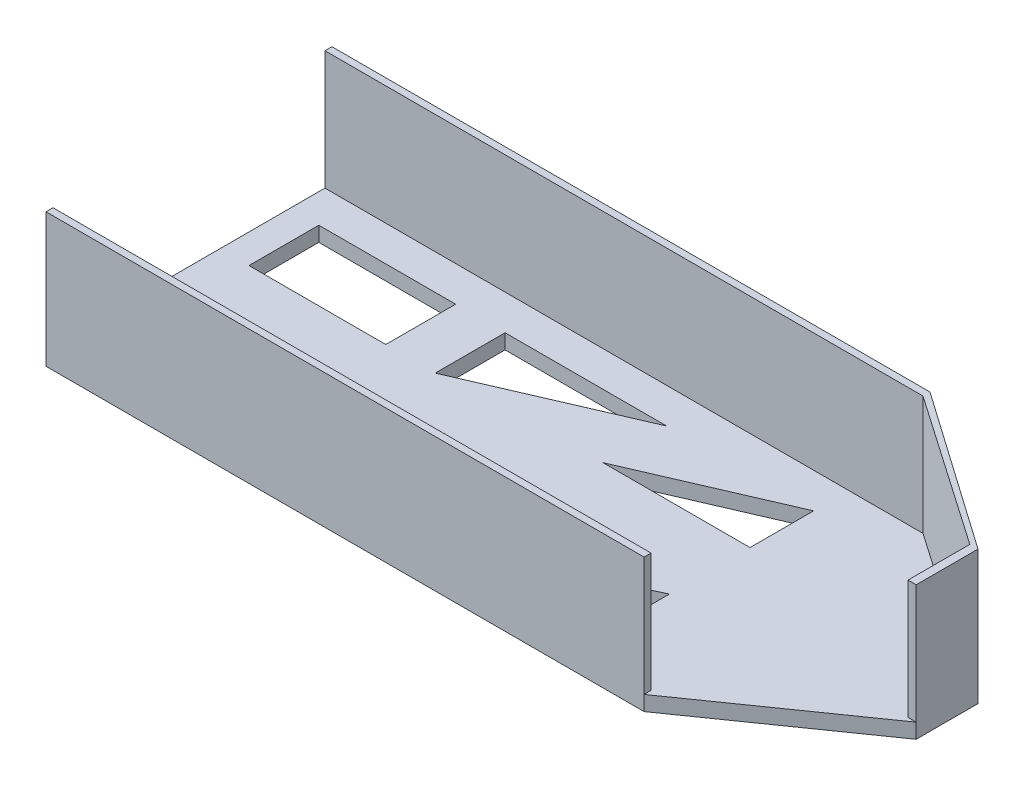
SolidWorks part; units mm, degrees
ref_plane "Front Plane" through (0, 0, 0) normal (0, 0, 1) x (1, 0, 0)
ref_plane "Top Plane" through (0, 0, 0) normal (0, 1, 0) x (1, 0, 0)
ref_plane "Right Plane" through (0, 0, 0) normal (1, 0, 0) x (0, 0, -1)
sketch "Sketch2" plane through (0, 0, 0) normal (0, 1, 0) x (1, 0, 0)
  line L0 (0, 48.8409) -> (27.3409, 29.7022)
  line L1 (-102.1557, 48.8409) -> (0, 48.8409)
  line L2 (-102.1557, 48.8409) -> (-102.1557, 0)
  line L3 (-102.1557, 0) -> (0, 0)
  line L5 (27.3409, 29.7022) -> (27.3409, 19.1387)
  line L6 (-102.1557, 24.4204) -> (100.6644, 24.4204) construction
  line L7 (0, 0) -> (27.3409, 19.1387)
  line L8 (-97.1846, 5.0954) -> (-97.1846, 17.026)
  line L9 (-97.1846, 41.6328) -> (-73.8206, 41.6328)
  line L10 (-97.1846, 41.6328) -> (-97.1846, 29.7022)
  line L11 (-97.1846, 29.7022) -> (-73.8206, 29.7022)
  line L12 (-73.8206, 41.6328) -> (-73.8206, 29.7022)
  line L13 (-97.1846, 17.026) -> (-73.8206, 17.026)
  line L14 (-73.8206, 17.026) -> (-97.1846, 5.0954)
  line L15 (-65.3697, 41.6328) -> (-65.3697, 29.7022)
  line L16 (-65.3697, 29.7022) -> (-37.7802, 41.6328)
  line L17 (-37.7802, 41.6328) -> (-65.3697, 41.6328)
  line L18 (-12.6763, 30.777) -> (-12.6763, 41.6328)
  line L19 (-12.6763, 41.6328) -> (-37.7802, 30.777)
  line L20 (-37.7802, 30.777) -> (-12.6763, 30.777)
  line L21 (-65.3697, 17.026) -> (-65.3697, 5.0954)
  line L22 (-65.3697, 5.0954) -> (-88.2367, 5.0954)
  line L23 (-88.2367, 5.0954) -> (-65.3697, 17.026)
  line L24 (-56.6703, 17.026) -> (-56.6703, 5.0954)
  line L25 (-56.6703, 5.0954) -> (-37.7802, 17.026)
  line L26 (-37.7802, 17.026) -> (-56.6703, 17.026)
  line L27 (-37.7802, 5.0954) -> (-12.6763, 5.0954)
  line L28 (-12.6763, 5.0954) -> (-12.6763, 17.026)
  line L29 (-12.6763, 17.026) -> (-37.7802, 5.0954)
  point P10 (27.3409, 24.4204)
extrude "Boss-Extrude1" add sketch "Sketch2" along normal blind 2.54
sketch "Sketch3" plane through (0, 2.54, 0) normal (0, 1, 0) x (1, 0, 0)
  line L0 (-102.1557, 24.4204) -> (35.6807, 24.4204) construction
  line L1 (-102.1557, 48.8409) -> (0, 48.8409)
  line L2 (-102.1557, 48.8409) -> (-102.1557, 47.646)
  line L3 (-102.1557, 47.646) -> (0, 47.646)
  line L5 (-102.1557, 48.8409) -> (-102.1557, 0) construction
  line L6 (27.3409, 29.7022) -> (25.9463, 29.7022) construction
  line L9 (25.9463, 29.7022) -> (0, 47.646)
  line L10 (0, 29.7022) -> (-3.1243, 29.7022) construction
  line L11 (25.9463, 29.7022) -> (25.9463, 19.1387)
  line L12 (25.9463, 24.4204) -> (27.3409, 24.4204)
  line L13 (27.3409, 19.1387) -> (27.3409, 29.7022) construction
  line L14 (27.3409, 19.1387) -> (27.3409, 29.7022)
  line L15 (27.3409, 29.7022) -> (0, 48.8409)
  line L16 (-102.1557, 0) -> (-102.1557, 1.1949)
  line L17 (-102.1557, 1.1949) -> (0, 1.1949)
  line L20 (-102.1557, 0) -> (0, 0)
  line L21 (0, 1.1949) -> (0, 0)
  line L22 (27.3409, 19.1387) -> (25.9463, 19.1387)
extrude "Boss-Extrude3" add sketch "Sketch3" along normal blind 20.32 contours L3 L9 L11 L22 L14 L15 L1 L2 | L17 L21 L20 L16
scale "Scale1" scale about centroid uniform scaling yes scale factor 0.6
